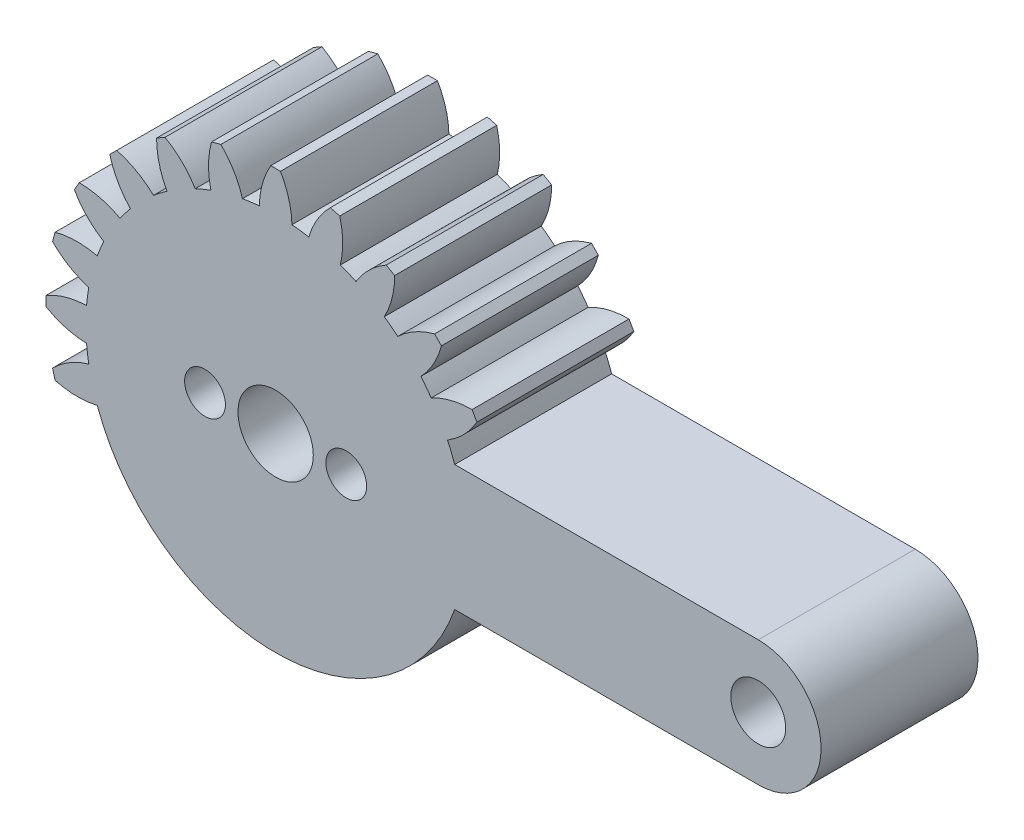
SolidWorks part; units mm, degrees
ref_plane "Front Plane" through (0, 0, 0) normal (0, 0, 1) x (1, 0, 0)
ref_plane "Top Plane" through (0, 0, 0) normal (0, 1, 0) x (1, 0, 0)
ref_plane "Right Plane" through (0, 0, 0) normal (1, 0, 0) x (0, 0, -1)
sketch "Sketch2" plane through (0, 0, 0) normal (0, 0, 1) x (1, 0, 0)
  line L0 (0, 0) -> (30.75, 0) construction
  line L1 (0, -14.63) -> (0, 14.63) construction
  line L2 (-0.31, 14.63) -> (0.31, 14.63)
  line L3 (3.4871, 14.2117) -> (4.086, 14.0513)
  line L4 (7.0465, 12.825) -> (7.5835, 12.515)
  line L5 (10.1258, 10.5642) -> (10.5642, 10.1258)
  line L6 (12.515, 7.5835) -> (12.825, 7.0465)
  line L9 (14.0743, -4) -> (14.0513, -4.086)
  line L10 (12.825, -7.0465) -> (12.515, -7.5835)
  line L11 (10.5642, -10.1258) -> (10.1258, -10.5642)
  line L12 (7.5835, -12.515) -> (7.0465, -12.825)
  line L13 (4.086, -14.0513) -> (3.4871, -14.2117)
  line L14 (0.31, -14.63) -> (-0.31, -14.63)
  line L15 (-3.4871, -14.2117) -> (-4.086, -14.0513)
  line L16 (-7.0465, -12.825) -> (-7.5835, -12.515)
  line L17 (-10.1258, -10.5642) -> (-10.5642, -10.1258)
  line L18 (-12.515, -7.5835) -> (-12.825, -7.0465)
  line L19 (-14.0513, -4.086) -> (-14.2117, -3.4871)
  line L20 (-14.63, -0.31) -> (-14.63, 0.31)
  line L21 (-14.2117, 3.4871) -> (-14.0513, 4.086)
  line L22 (-12.825, 7.0465) -> (-12.515, 7.5835)
  line L23 (-10.5642, 10.1258) -> (-10.1258, 10.5642)
  line L24 (-7.5835, 12.515) -> (-7.0465, 12.825)
  line L25 (-4.086, 14.0513) -> (-3.4871, 14.2117)
  line L26 (30.75, -4) -> (30.75, 4) construction
  line L27 (30.75, 4) -> (11.4091, 4)
  line L28 (30.75, -4) -> (11.4091, -4)
  line L29 (14.63, 0) -> (14.63, -0.31) [skipped]
  line L30 (14.0513, 4.086) -> (14.0743, 4) [skipped]
  circle A0 centre (0, 0) radius 12.09
  circle A1 centre (0, 0) radius 1.75
  circle A2 centre (30.75, 0) radius 1.75
  arc A3 (-1.04, 12.0452) -> (-0.31, 14.63) centre (4.3585, 11.9161) cw
  arc A4 (1.04, 12.0452) -> (0.31, 14.63) centre (-4.3585, 11.9161) ccw
  arc A5 (4.1221, 11.3656) -> (4.086, 14.0513) centre (-1.1258, 12.6381) ccw
  arc A6 (2.113, 11.9039) -> (3.4871, 14.2117) centre (7.294, 10.382) cw
  arc A7 (6.9233, 9.9114) -> (7.5835, 12.515) centre (2.1835, 12.4988) ccw
  arc A8 (5.1219, 10.9514) -> (7.0465, 12.825) centre (9.7326, 8.1404) cw
  arc A9 (9.2526, 7.7818) -> (10.5642, 10.1258) centre (5.344, 11.5078) ccw
  arc A10 (7.7818, 9.2526) -> (10.1258, 10.5642) centre (11.5078, 5.344) cw
  arc A11 (10.9514, 5.1219) -> (12.825, 7.0465) centre (8.1404, 9.7326) ccw
  arc A12 (9.9114, 6.9233) -> (12.515, 7.5835) centre (12.4988, 2.1835) cw
  arc A19 (9.9114, -6.9233) -> (12.515, -7.5835) centre (12.4988, -2.1835) ccw
  arc A20 (10.9514, -5.1219) -> (12.825, -7.0465) centre (8.1404, -9.7326) cw
  arc A21 (7.7818, -9.2526) -> (10.1258, -10.5642) centre (11.5078, -5.344) ccw
  arc A22 (9.2526, -7.7818) -> (10.5642, -10.1258) centre (5.344, -11.5078) cw
  arc A23 (5.1219, -10.9514) -> (7.0465, -12.825) centre (9.7326, -8.1404) ccw
  arc A24 (6.9233, -9.9114) -> (7.5835, -12.515) centre (2.1835, -12.4988) cw
  arc A25 (2.113, -11.9039) -> (3.4871, -14.2117) centre (7.294, -10.382) ccw
  arc A26 (4.1221, -11.3656) -> (4.086, -14.0513) centre (-1.1258, -12.6381) cw
  arc A27 (-1.04, -12.0452) -> (-0.31, -14.63) centre (4.3585, -11.9161) ccw
  arc A28 (1.04, -12.0452) -> (0.31, -14.63) centre (-4.3585, -11.9161) cw
  arc A29 (-4.1221, -11.3656) -> (-4.086, -14.0513) centre (1.1258, -12.6381) ccw
  arc A30 (-2.113, -11.9039) -> (-3.4871, -14.2117) centre (-7.294, -10.382) cw
  arc A31 (-6.9233, -9.9114) -> (-7.5835, -12.515) centre (-2.1835, -12.4988) ccw
  arc A32 (-5.1219, -10.9514) -> (-7.0465, -12.825) centre (-9.7326, -8.1404) cw
  arc A33 (-9.2526, -7.7818) -> (-10.5642, -10.1258) centre (-5.344, -11.5078) ccw
  arc A34 (-7.7818, -9.2526) -> (-10.1258, -10.5642) centre (-11.5078, -5.344) cw
  arc A35 (-10.9514, -5.1219) -> (-12.825, -7.0465) centre (-8.1404, -9.7326) ccw
  arc A36 (-9.9114, -6.9233) -> (-12.515, -7.5835) centre (-12.4988, -2.1835) cw
  arc A37 (-11.9039, -2.113) -> (-14.2117, -3.4871) centre (-10.382, -7.294) ccw
  arc A38 (-11.3656, -4.1221) -> (-14.0513, -4.086) centre (-12.6381, 1.1258) cw
  arc A39 (-12.0452, 1.04) -> (-14.63, 0.31) centre (-11.9161, -4.3585) ccw
  arc A40 (-12.0452, -1.04) -> (-14.63, -0.31) centre (-11.9161, 4.3585) cw
  arc A41 (-11.3656, 4.1221) -> (-14.0513, 4.086) centre (-12.6381, -1.1258) ccw
  arc A42 (-11.9039, 2.113) -> (-14.2117, 3.4871) centre (-10.382, 7.294) cw
  arc A43 (-9.9114, 6.9233) -> (-12.515, 7.5835) centre (-12.4988, 2.1835) ccw
  arc A44 (-10.9514, 5.1219) -> (-12.825, 7.0465) centre (-8.1404, 9.7326) cw
  arc A45 (-7.7818, 9.2526) -> (-10.1258, 10.5642) centre (-11.5078, 5.344) ccw
  arc A46 (-9.2526, 7.7818) -> (-10.5642, 10.1258) centre (-5.344, 11.5078) cw
  arc A47 (-5.1219, 10.9514) -> (-7.0465, 12.825) centre (-9.7326, 8.1404) ccw
  arc A48 (-6.9233, 9.9114) -> (-7.5835, 12.515) centre (-2.1835, 12.4988) cw
  arc A49 (-2.113, 11.9039) -> (-3.4871, 14.2117) centre (-7.294, 10.382) ccw
  arc A50 (-4.1221, 11.3656) -> (-4.086, 14.0513) centre (1.1258, 12.6381) cw
  arc A51 (30.75, -4) -> (30.75, 4) centre (30.75, 0) ccw
  arc A52 (11.3656, -4.1221) -> (14.0513, -4.086) centre (12.6381, 1.1258) ccw [skipped]
  arc A53 (11.9039, -2.113) -> (14.2117, -3.4871) centre (10.382, -7.294) cw [skipped]
  arc A54 (12.0452, -1.04) -> (14.63, -0.31) centre (11.9161, 4.3585) ccw [skipped]
  arc A55 (12.0452, 1.04) -> (14.63, 0.31) centre (11.9161, -4.3585) cw [skipped]
  arc A56 (11.9039, 2.113) -> (14.2117, 3.4871) centre (10.382, 7.294) ccw [skipped]
  arc A57 (11.3656, 4.1221) -> (14.0513, 4.086) centre (12.6381, -1.1258) cw [skipped]
  point P9 (0, 0)
  point P157 (30.75, 0)
  dimension "D2" = 3.5
  dimension "D3" = 3.5
  dimension "D4" = 24.18
  dimension "D6" = 5.4
  dimension "D10" = 8
  dimension "D1" = 30.75
  dimension "D5" = 29.26
  dimension "D7" = 0.31
  dimension "D8" = 1.04
  dimension "D9" = 24
extrude "Boss-Extrude1" add sketch "Sketch2" along normal blind 10 contours A0 A1 | L28 A51 L27 A0 A2 | A12 A0 A11 L6 | A10 A0 A9 L5 | A8 A0 A7 L4 | A6 A0 A5 L3 | A0 A4 L2 A3 | A50 A0 A49 L25 | A48 A0 A47 L24 | A46 A0 A45 L23 | A44 A0 A43 L22 | A42 A0 A41 L21 | A40 A0 A39 L20 | A38 A0 A37 L19
sketch "Sketch3" plane through (0, 0, 10) normal (0, 0, 1) x (1, 0, 0)
  line L0 (-4.5, 0) -> (4.5, 0) construction
  circle A0 centre (-4.5, 0) radius 1.3
  circle A1 centre (4.5, 0) radius 1.3
  circle A2 centre (0, 0) radius 2.4
  point P6 (0, 0)
  dimension "D2" = 2.6
  dimension "D3" = 2.6
  dimension "D4" = 4.8
  dimension "D1" = 9
extrude "Cut-Extrude1" cut sketch "Sketch3" against normal through all
